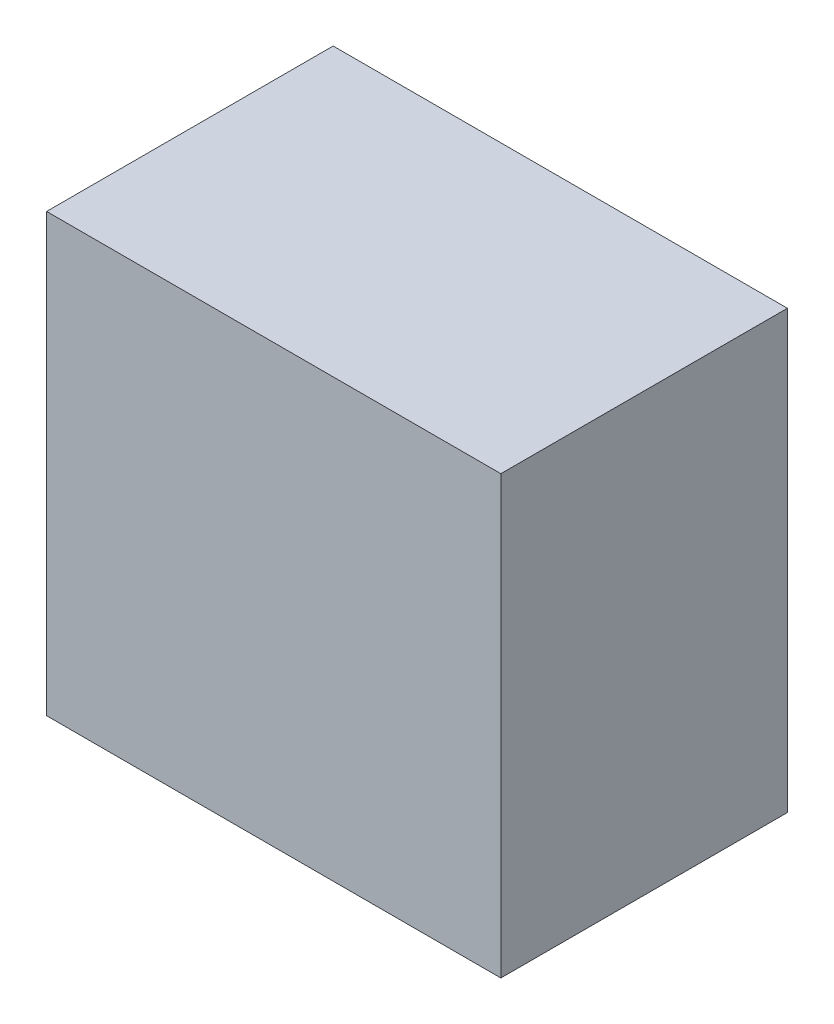
SolidWorks part; units mm, degrees
ref_plane "Front Plane" through (0, 0, 0) normal (0, 0, 1) x (1, 0, 0)
ref_plane "Top Plane" through (0, 0, 0) normal (0, 1, 0) x (1, 0, 0)
ref_plane "Right Plane" through (0, 0, 0) normal (1, 0, 0) x (0, 0, -1)
sketch "Sketch1" plane through (0, 0, 0) normal (0, 0, 1) x (1, 0, 0)
  line L1 (0, 0) -> (31.7045, 0)
  line L2 (0, 0) -> (0, 30.4851)
  line L3 (0, 30.4851) -> (31.7045, 30.4851)
  line L4 (31.7045, 0) -> (31.7045, 30.4851)
extrude "Boss-Extrude1" add sketch "Sketch1" along normal blind 20
